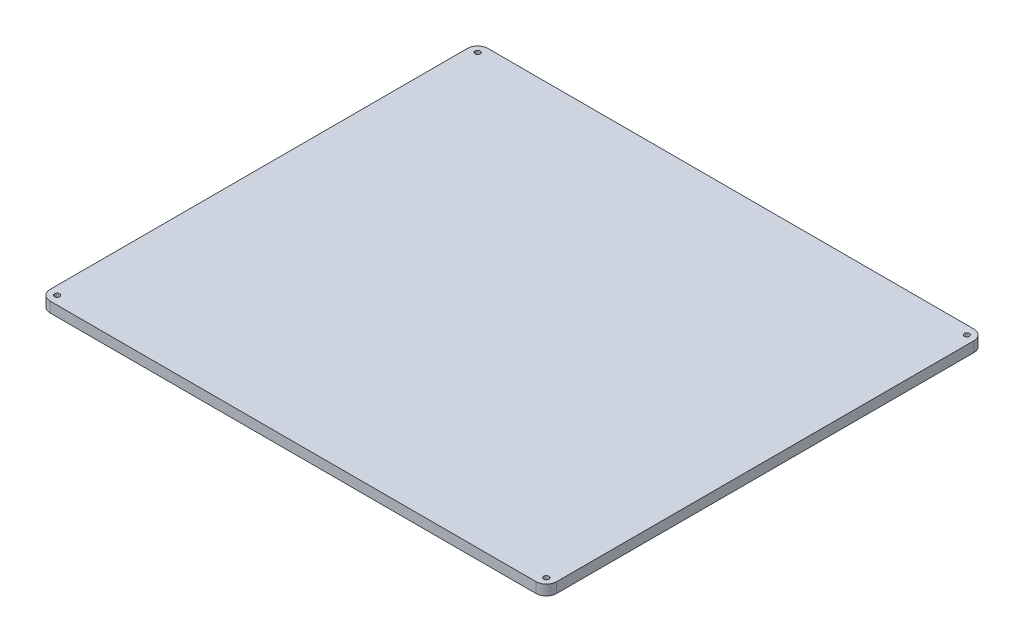
SolidWorks part; units mm, degrees
ref_plane "Alzado" through (0, 0, 0) normal (0, 0, 1) x (1, 0, 0)
ref_plane "Planta" through (0, 0, 0) normal (0, 1, 0) x (1, 0, 0)
ref_plane "Vista lateral" through (0, 0, 0) normal (1, 0, 0) x (0, 0, -1)
sketch "Croquis2" plane through (0, 0, 0) normal (0, 1, 0) x (1, 0, 0)
  line L3 (-121.4956, 121.75) -> (161.5044, 121.75)
  line L5 (167.5044, 115.75) -> (167.5044, -127.25)
  line L6 (-121.4956, -133.25) -> (161.5044, -133.25)
  line L7 (-127.4956, 115.75) -> (-127.4956, -127.25)
  circle A0 centre (162.5044, 116.75) radius 1.5
  arc A1 (167.5044, -127.25) -> (161.5044, -133.25) centre (161.5044, -127.25) cw
  arc A2 (-121.4956, -133.25) -> (-127.4956, -127.25) centre (-121.4956, -127.25) cw
  arc A3 (-127.4956, 115.75) -> (-121.4956, 121.75) centre (-121.4956, 115.75) cw
  arc A4 (167.5044, 115.75) -> (161.5044, 121.75) centre (161.5044, 115.75) ccw
  circle A5 centre (162.5044, -128.25) radius 1.5
  circle A6 centre (-122.4956, -128.25) radius 1.5
  circle A7 centre (-122.4956, 116.75) radius 1.5
  dimension "D1" = 6
  dimension "D2" = 6
  dimension "D3" = 6
  dimension "D4" = 6
  dimension "D5" = 283
  dimension "D7" = 285
  dimension "D8" = 245
extrude "Saliente-Extruir1" add sketch "Croquis2" along normal blind 6
